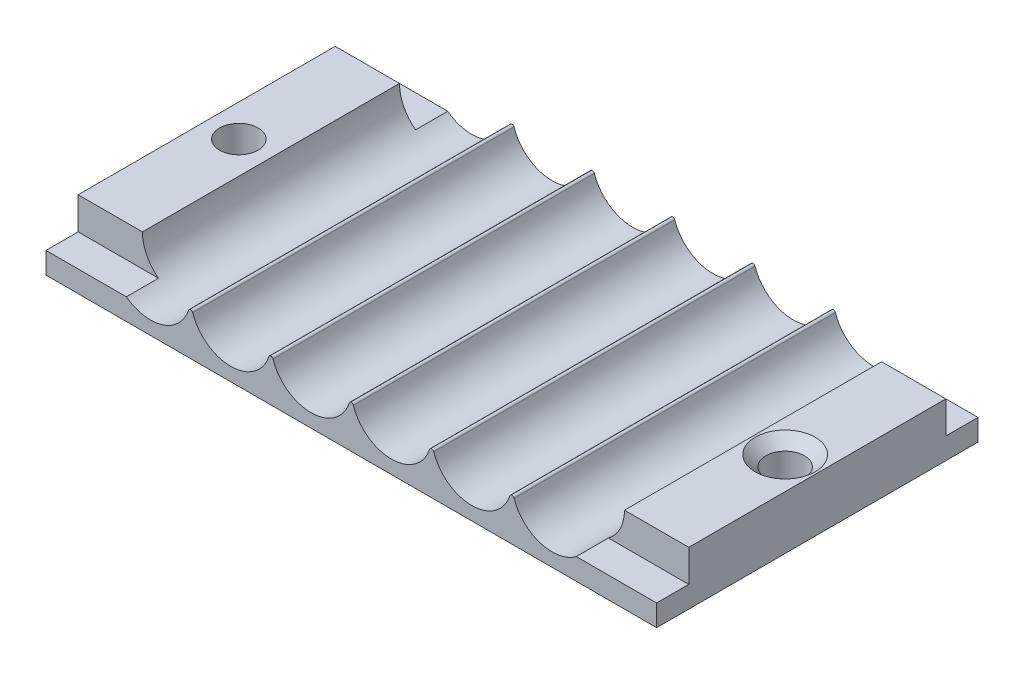
SolidWorks part; units mm, degrees
ref_plane "Plano frontal" through (0, 0, 0) normal (0, 0, 1) x (1, 0, 0)
ref_plane "Plano superior" through (0, 0, 0) normal (0, 1, 0) x (1, 0, 0)
ref_plane "Plano direito" through (0, 0, 0) normal (1, 0, 0) x (0, 0, -1)
sketch "Esboço1" plane through (0, 0, 0) normal (0, 0, 1) x (1, 0, 0)
  line L0 (-22.5, 5) -> (-22.5, 0) construction
  line L1 (-22.5, 0) -> (22.5, 0)
  line L2 (22.5, 0) -> (22.5, 5) construction
  line L3 (-22.5, 5) -> (22.5, 5) construction
  line L4 (-22.5, 5) -> (-28.5, 5)
  line L5 (-28.5, 5) -> (-28.5, 0)
  line L6 (-28.5, 0) -> (-22.5, 0)
  line L7 (0, -55) -> (0, 55) construction
  line L8 (28.5, 0) -> (22.5, 0)
  line L9 (28.5, 5) -> (28.5, 0)
  line L10 (22.5, 5) -> (28.5, 5)
  arc A0 (-22.5, 5) -> (-15, 5) centre (-18.75, 5) ccw
  arc A1 (-15, 5) -> (-7.5, 5) centre (-11.25, 5) ccw
  arc A2 (-7.5, 5) -> (0, 5) centre (-3.75, 5) ccw
  arc A3 (0, 5) -> (7.5, 5) centre (3.75, 5) ccw
  arc A4 (7.5, 5) -> (15, 5) centre (11.25, 5) ccw
  arc A5 (15, 5) -> (22.5, 5) centre (18.75, 5) ccw
  point P2 (0, 0)
  dimension "D1" = 7.5
  dimension "D3" = 5
  dimension "D4" = 6
  dimension "D2" = 6
extrude "Ressalto-extrusão1" add sketch "Esboço1" along normal mid plane 30
sketch "Esboço2" plane through (0, 5, 0) normal (0, 1, 0) x (1, 0, 0)
  line L0 (-22.5, 15) -> (-28.5, 15) construction
  line L1 (-28.5, -15) -> (-28.5, 15) construction
  line L2 (0, -2.75) -> (0, 2.75) construction
  circle A0 centre (-25.5, 0) radius 1.8
  circle A1 centre (25.5, 0) radius 1.8
  point P2 (0, 0)
  point P5 (-25.5, 15)
  point P8 (-28.5, 0)
  dimension "D1" = 3.6
extrude "Corte-extrusão1" cut sketch "Esboço2" against normal through all
sketch "Esboço3" plane through (0, 5, 0) normal (0, 1, 0) x (1, 0, 0)
  line L18 (-15, 15) -> (-22.5, 15) construction
  line L19 (-28.5, 15) -> (-18.75, 15)
  line L20 (-28.5, 15) -> (-28.5, 12)
  line L21 (-28.5, 12) -> (-18.75, 12)
  line L22 (-18.75, 15) -> (-18.75, 12)
  line L23 (0, -15) -> (0, 15) construction
  line L24 (-28.5, -15) -> (-18.75, -15)
  line L25 (-28.5, -15) -> (-28.5, -12)
  line L26 (-28.5, -12) -> (-18.75, -12)
  line L27 (-18.75, -15) -> (-18.75, -12)
  line L28 (18.75, -15) -> (18.75, -12)
  line L29 (28.5, -12) -> (18.75, -12)
  line L30 (28.5, -15) -> (28.5, -12)
  line L31 (28.5, -15) -> (18.75, -15)
  line L32 (18.75, 15) -> (18.75, 12)
  line L33 (28.5, 12) -> (18.75, 12)
  line L34 (28.5, 15) -> (28.5, 12)
  line L35 (28.5, 15) -> (18.75, 15)
  point P7 (-18.75, 15)
  dimension "D1" = 3
extrude "Corte-extrusão2" cut sketch "Esboço3" against normal blind 3
fillet "Filete1" radius 0.2 5 edges at (15, 5, 0) (7.5, 5, 0) (0, 5, 0) (-7.5, 5, 0) (-15, 5, 0)
chamfer "Chanfro1" distance 1 angle 45 3 edges at (27.3, 5, 0) (27.3, 0, 0) (-27.3, 0, 0)
